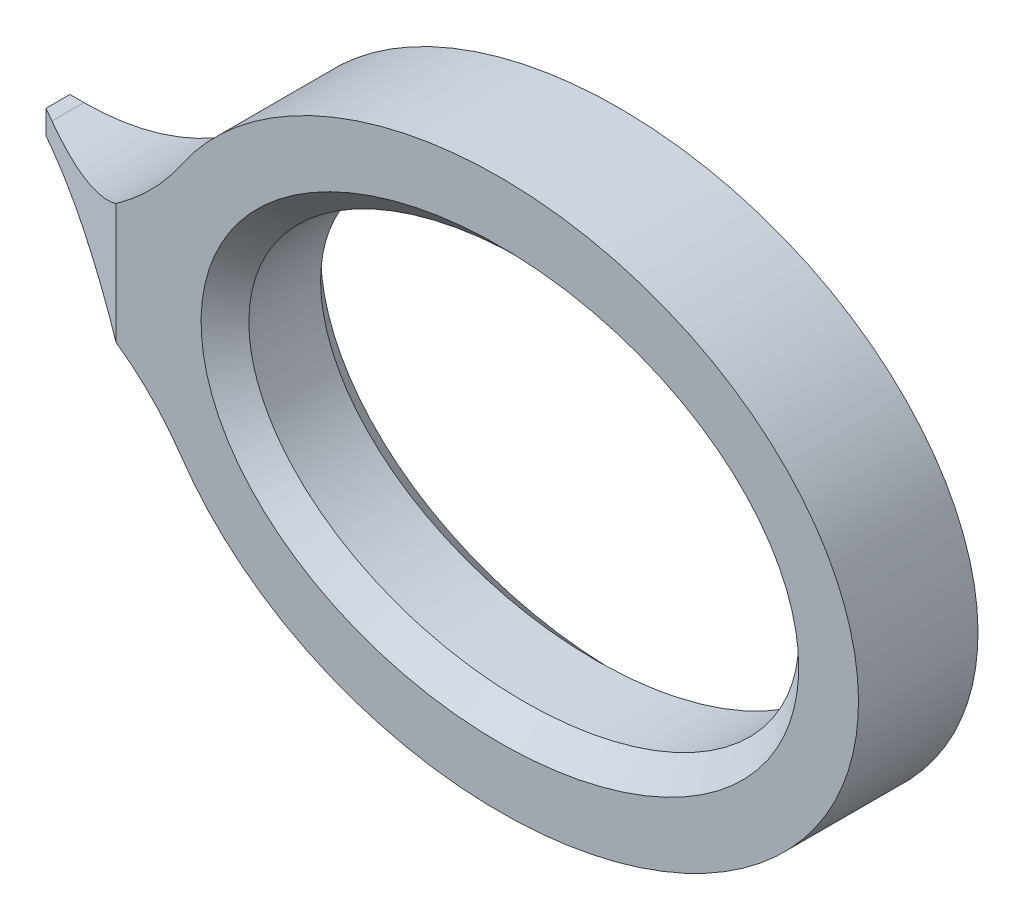
SolidWorks part; units mm, degrees
ref_plane "Front Plane" through (0, 0, 0) normal (0, 0, 1) x (1, 0, 0)
ref_plane "Top Plane" through (0, 0, 0) normal (0, 1, 0) x (1, 0, 0)
ref_plane "Right Plane" through (0, 0, 0) normal (1, 0, 0) x (0, 0, -1)
sketch "Sketch1" plane through (0, 0, 0) normal (0, 0, 1) x (1, 0, 0)
  line L0 (-11.5, 0) -> (11.5, 0) construction
  line L1 (-15, 0) -> (15, 0) construction
  line L2 (-22.3983, 0.5) -> (-22.9858, 0.5)
  line L3 (-22.9858, 0.5) -> (-22.9858, -0.5)
  line L4 (-22.9858, -0.5) -> (-22.3983, -0.5)
  line L5 (-14.9858, -0.5) -> (-14.9858, 0.5) construction
  arc A0 (-22.3983, -0.5) -> (-13.3015, -5.3154) centre (-22.3983, -11.5) cw
  arc A1 (-22.3983, 0.5) -> (-13.3015, 5.3154) centre (-22.3983, 11.5) ccw
  ellipse E0 centre (0, 0) end of major axis (11.5, 0) minor radius 8
  ellipse E1 centre (0, 0) end of major axis (15, 0) minor radius 11.5 (-13.3015, -5.3154) -> (-13.3015, 5.3154) ccw
  point P7 (-14.9858, 0)
  point P20 (-22.9858, 0)
  dimension "D7" = 11
  dimension "D1" = 16
  dimension "D2" = 23
  dimension "D3" = 30
  dimension "D4" = 23
  dimension "D5" = 1
  dimension "D6" = 8
extrude "Boss-Extrude1" add sketch "Sketch1" along normal blind 5
chamfer "Chamfer1" distance 1 angle 45 2 edges at (11.5, 0, 0) (11.5, 0, 5)
chamfer "Chamfer2" distance 4 angle 60 1 edges at (-22.9858, 0, 5)
